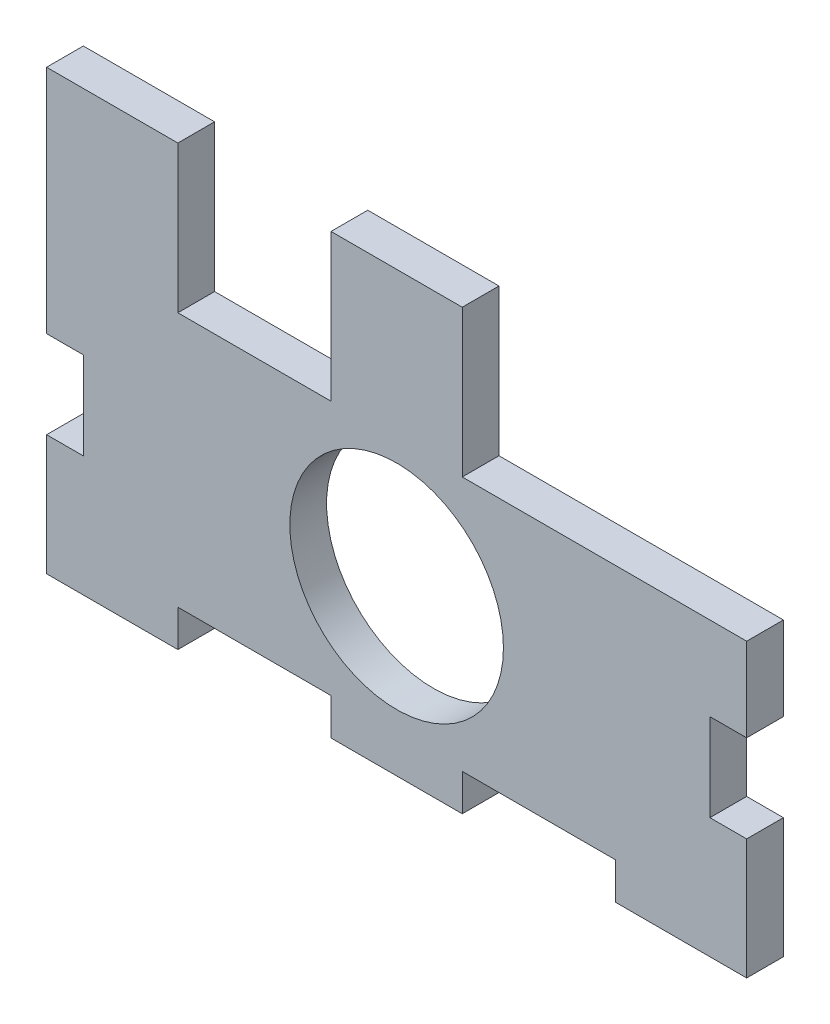
SolidWorks part; units mm, degrees
ref_plane "Front Plane" through (0, 0, 0) normal (0, 0, 1) x (1, 0, 0)
ref_plane "Top Plane" through (0, 0, 0) normal (0, 1, 0) x (1, 0, 0)
ref_plane "Right Plane" through (0, 0, 0) normal (1, 0, 0) x (0, 0, -1)
sketch "Sketch1" plane through (0, 0, 0) normal (0, 0, 1) x (1, 0, 0)
  line L1 (-50.8, 18.5) -> (50.8, 18.5)
  line L2 (-50.8, 18.5) -> (-50.8, -18.5)
  line L3 (-50.8, -18.5) -> (50.8, -18.5)
  line L4 (50.8, 18.5) -> (50.8, -18.5)
  line L5 (-50.8, 18.5) -> (50.8, -18.5) construction
  line L6 (-50.8, -18.5) -> (50.8, 18.5) construction
  point P0 (0, 0)
  dimension "D1" = 37
  dimension "D2" = 101.6
extrude "Boss-Extrude1" add sketch "Sketch1" along normal blind 5.334
sketch "Sketch2" plane through (0, 0, 5.334) normal (0, 0, 1) x (1, 0, 0)
  line L0 (0, 0) -> (0, 50000) construction
  line L1 (0, 0) -> (50000, 0) construction
  circle A0 centre (0, 0) radius 15.5
  dimension "D1" = 31
extrude "MotorHoles" cut sketch "Sketch2" against normal through all
sketch "Sketch3" plane through (0, -18.5, 0) normal (0, -1, 0) x (1, 0, 0)
  line L0 (-50.8, 0) -> (50.8, 0) construction
  line L1 (-50.8, 5.334) -> (-31.75, 5.334)
  line L2 (-50.8, 5.334) -> (-50.8, 0)
  line L3 (-50.8, 0) -> (-31.75, 0)
  line L4 (-31.75, 5.334) -> (-31.75, 0)
  line L5 (0, 0) -> (0, -50000) construction
  line L6 (31.75, 5.334) -> (31.75, 0)
  line L7 (-9.525, 5.334) -> (9.525, 5.334)
  line L8 (-9.525, 5.334) -> (-9.525, 0)
  line L9 (-9.525, 0) -> (9.525, 0)
  line L10 (9.525, 5.334) -> (9.525, 0)
  line L11 (-9.525, 5.334) -> (9.525, 0) construction
  line L12 (-9.525, 0) -> (9.525, 5.334) construction
  line L13 (50.8, 0) -> (31.75, 0)
  line L14 (50.8, 5.334) -> (50.8, 0)
  line L15 (50.8, 5.334) -> (31.75, 5.334)
  point P10 (0, 2.667)
  dimension "D1" = 19.05
  dimension "D2" = 19.05
  dimension "D3" = 22.225
extrude "BottomTeeth" add sketch "Sketch3" along normal blind 5.334
sketch "Sketch4" plane through (0, 0, 5.334) normal (0, 0, 1) x (1, 0, 0)
  line L0 (0, 0) -> (-50000, 0) construction
  line L1 (-50.8, 18.5) -> (-50.8, -23.834) construction
  line L2 (-56.134, 6.35) -> (-45.466, 6.35)
  line L3 (-56.134, 6.35) -> (-56.134, -6.35)
  line L4 (-56.134, -6.35) -> (-45.466, -6.35)
  line L5 (-45.466, 6.35) -> (-45.466, -6.35)
  line L6 (-56.134, 6.35) -> (-45.466, -6.35) construction
  line L7 (-56.134, -6.35) -> (-45.466, 6.35) construction
  line L8 (0, 0) -> (0, -50000) construction
  line L9 (56.134, -6.35) -> (45.466, 6.35) construction
  line L10 (56.134, 6.35) -> (45.466, -6.35) construction
  line L11 (45.466, 6.35) -> (45.466, -6.35)
  line L12 (56.134, -6.35) -> (45.466, -6.35)
  line L13 (56.134, 6.35) -> (56.134, -6.35)
  line L14 (56.134, 6.35) -> (45.466, 6.35)
  point P3 (-50.8, 0)
  point P16 (50.8, 0)
  dimension "D1" = 10.668
  dimension "D2" = 12.7
extrude "SideCut" cut sketch "Sketch4" against normal through all
sketch "Sketch5" plane through (0, 18.5, 0) normal (0, 1, 0) x (1, 0, 0)
  line L0 (50.8, -5.334) -> (-50.8, -5.334) construction
  line L1 (-50.8, 0) -> (-31.75, 0)
  line L2 (-50.8, 0) -> (-50.8, -5.334)
  line L3 (-50.8, -5.334) -> (-31.75, -5.334)
  line L4 (-31.75, 0) -> (-31.75, -5.334)
  line L5 (0, 0) -> (0, -50000) construction
  line L7 (-9.525, 0) -> (9.525, 0)
  line L8 (-9.525, 0) -> (-9.525, -5.334)
  line L9 (-9.525, -5.334) -> (9.525, -5.334)
  line L10 (9.525, 0) -> (9.525, -5.334)
  line L11 (-9.525, 0) -> (9.525, -5.334) construction
  line L12 (-9.525, -5.334) -> (9.525, 0) construction
  point P10 (0, -2.667)
  dimension "D1" = 19.05
  dimension "D2" = 19.05
  dimension "D3" = 22.225
extrude "TopTeeth" add sketch "Sketch5" along normal blind 21.336
